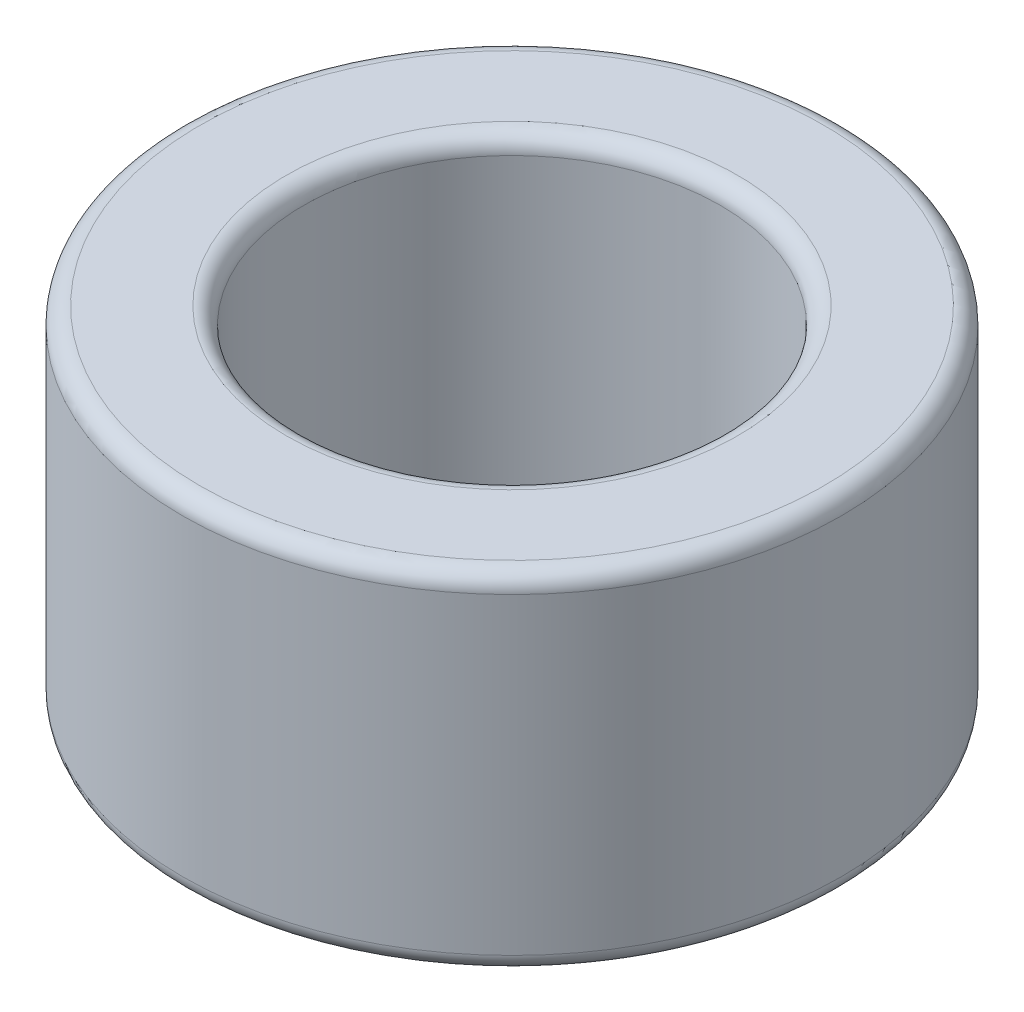
SolidWorks part; units mm, degrees
ref_plane "Front Plane" through (0, 0, 0) normal (0, 0, 1) x (1, 0, 0)
ref_plane "Top Plane" through (0, 0, 0) normal (0, 1, 0) x (1, 0, 0)
ref_plane "Right Plane" through (0, 0, 0) normal (1, 0, 0) x (0, 0, -1)
sketch "Sketch1" plane through (0, 0, 0) normal (0, 1, 0) x (1, 0, 0)
  circle A0 centre (0, 0) radius 4.745
  circle A1 centre (0, 0) radius 3
  dimension "D1" = 6
  dimension "D2" = 9.49
extrude "Boss-Extrude1" add sketch "Sketch1" along normal blind 5
fillet "Fillet1" radius 0.25 4 edges at (0, 0, 3) (0, 5, 3) (0, 0, 4.745) (0, 5, 4.745)
